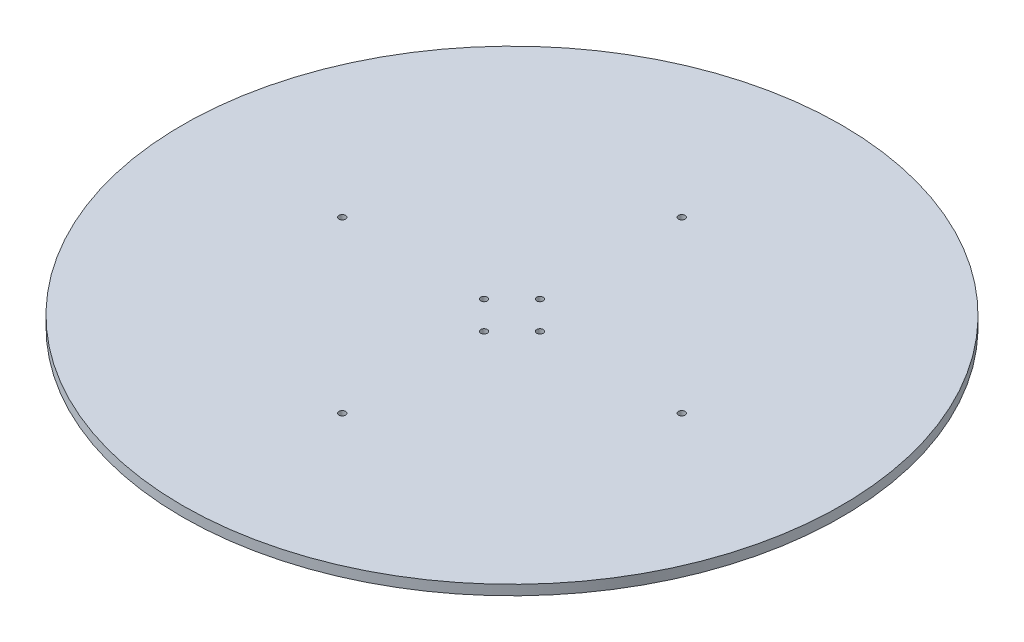
SolidWorks part; units mm, degrees
ref_plane "Alzado" through (0, 0, 0) normal (0, 0, 1) x (1, 0, 0)
ref_plane "Planta" through (0, 0, 0) normal (0, 1, 0) x (1, 0, 0)
ref_plane "Vista lateral" through (0, 0, 0) normal (1, 0, 0) x (0, 0, -1)
sketch "Sketch1" plane through (0, 0, 0) normal (0, 1, 0) x (1, 0, 0)
  line L0 (0, 0) -> (14, 0) construction
  circle A0 centre (0, 0) radius 165
  circle A1 centre (14, 0) radius 1.65
  circle A2 centre (0, -14) radius 1.65
  circle A3 centre (-14, 0) radius 1.65
  circle A4 centre (0, 14) radius 1.65
  circle A5 centre (85, 0) radius 1.65
  circle A6 centre (0, -85) radius 1.65
  circle A7 centre (-85, 0) radius 1.65
  circle A8 centre (0, 85) radius 1.65
  point P14 (0, 0)
  point P23 (0, 0)
  dimension "D1" = 330
  dimension "D3" = 3.3
  dimension "D2" = 14
  dimension "D5" = 2
  dimension "D4" = 4
  dimension "D6" = 4
extrude "Boss-Extrude1" add sketch "Sketch1" along normal blind 5
